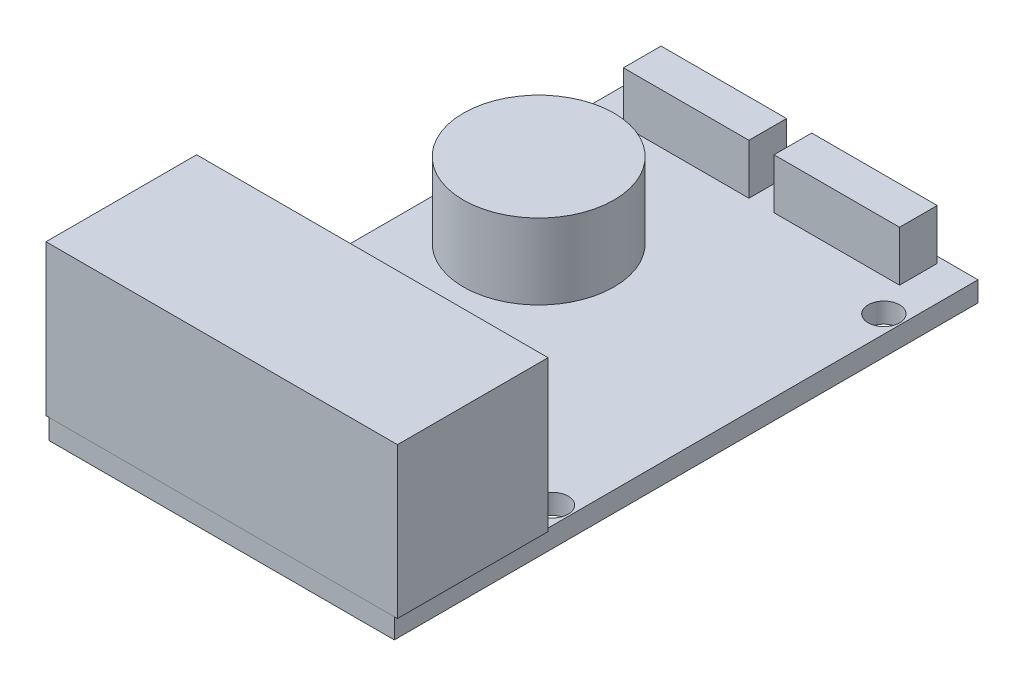
SolidWorks part; units mm, degrees
ref_plane "Front Plane" through (0, 0, 0) normal (0, 0, 1) x (1, 0, 0)
ref_plane "Top Plane" through (0, 0, 0) normal (0, 1, 0) x (1, 0, 0)
ref_plane "Right Plane" through (0, 0, 0) normal (1, 0, 0) x (0, 0, -1)
sketch "Sketch1" plane through (0, 0, 0) normal (0, 1, 0) x (1, 0, 0)
  line L0 (0, 23.25) -> (0, -23.25) construction
  line L1 (-13.75, 23.25) -> (13.75, 23.25)
  line L2 (-13.75, 23.25) -> (-13.75, -23.25)
  line L3 (-13.75, -23.25) -> (13.75, -23.25)
  line L4 (13.75, 23.25) -> (13.75, -23.25)
  point P6 (0, 0)
  dimension "D1" = 46.5
  dimension "D2" = 27.5
extrude "PCB" add sketch "Sketch1" along normal blind 1.6
sketch "Sketch2" plane through (0, 0, 23.25) normal (0, 0, 1) x (1, 0, 0)
  line L1 (-14, 13.6) -> (14, 13.6)
  line L2 (-14, 13.6) -> (-14, 1.6)
  line L3 (-14, 1.6) -> (14, 1.6)
  line L4 (14, 13.6) -> (14, 1.6)
  line L5 (-13.75, 1.6) -> (13.75, 1.6) construction
  line L6 (0, 13.6) -> (0, 0) construction
  dimension "D1" = 28
  dimension "D2" = 12
extrude "Scanner" add sketch "Sketch2" against normal blind 12 separate body
sketch "Sketch3" plane through (0, 1.6, 0) normal (0, 1, 0) x (1, 0, 0)
  line L0 (13.75, 23.25) -> (-13.75, 23.25) construction
  line L1 (-13.75, 23.25) -> (-13.75, -23.25) construction
  line L2 (-12.35, 17.15) -> (-12.35, -9.25) construction
  line L3 (0, 23.25) -> (0, 0) construction
  circle A0 centre (-12.35, 17.15) radius 1.25
  circle A1 centre (-12.35, -9.25) radius 1.25
  circle A2 centre (12.35, -9.25) radius 1.25
  circle A3 centre (12.35, 17.15) radius 1.25
  dimension "D1" = 2.5
  dimension "D2" = 6.1
  dimension "D3" = 1.4
  dimension "D4" = 26.4
extrude "Mounting Holes" cut sketch "Sketch3" against normal through all
sketch "Sketch4" plane through (0, 1.6, 0) normal (0, 1, 0) x (1, 0, 0)
  line L0 (13.75, 23.25) -> (-13.75, 23.25) construction
  line L1 (-13.75, 23.25) -> (-13.75, -23.25) construction
  circle A0 centre (-6.25, 8.25) radius 6
  dimension "D1" = 12
  dimension "D2" = 15
  dimension "D3" = 7.5
extrude "Piezo Buzzer" add sketch "Sketch4" along normal blind 6
sketch "Sketch5" plane through (0, 1.6, 0) normal (0, 1, 0) x (1, 0, 0)
  line L0 (0, 23.25) -> (0, 0) construction
  line L1 (-11, 22.75) -> (-1, 22.75)
  line L2 (-11, 22.75) -> (-11, 19.75)
  line L3 (-11, 19.75) -> (-1, 19.75)
  line L4 (-1, 22.75) -> (-1, 19.75)
  line L5 (13.75, 23.25) -> (-13.75, 23.25) construction
  line L6 (11, 19.75) -> (1, 19.75)
  line L7 (1, 22.75) -> (1, 19.75)
  line L8 (11, 22.75) -> (1, 22.75)
  line L9 (11, 22.75) -> (11, 19.75)
  dimension "D1" = 10
  dimension "D2" = 1
  dimension "D3" = 3
  dimension "D4" = 0.5
extrude "Connectors" add sketch "Sketch5" along normal blind 4
